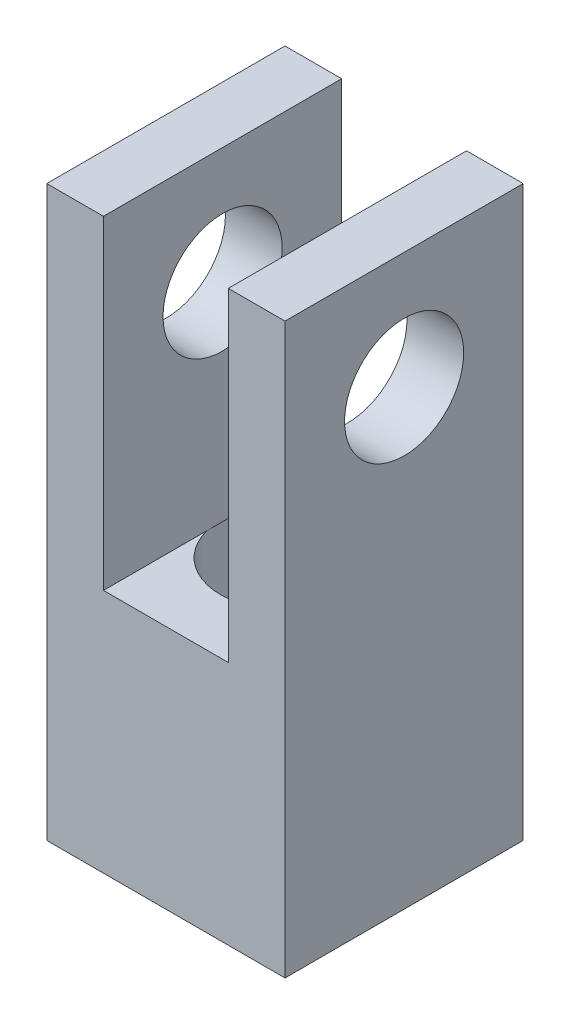
SolidWorks part; units mm, degrees
ref_plane "Front Plane" through (0, 0, 0) normal (0, 0, 1) x (1, 0, 0)
ref_plane "Top Plane" through (0, 0, 0) normal (0, 1, 0) x (1, 0, 0)
ref_plane "Right Plane" through (0, 0, 0) normal (1, 0, 0) x (0, 0, -1)
sketch "Sketch1" plane through (0, 0, 0) normal (0, 1, 0) x (1, 0, 0)
  line L1 (-6.35, -6.35) -> (6.35, -6.35)
  line L2 (-6.35, -6.35) -> (-6.35, 6.35)
  line L3 (-6.35, 6.35) -> (6.35, 6.35)
  line L4 (6.35, -6.35) -> (6.35, 6.35)
  line L5 (-6.35, -6.35) -> (6.35, 6.35) construction
  line L6 (-6.35, 6.35) -> (6.35, -6.35) construction
  point P0 (0, 0)
  dimension "D1" = 12.7
  dimension "D2" = 12.7
extrude "Boss-Extrude1" add sketch "Sketch1" along normal blind 30.3276
sketch "Sketch2" plane through (0, 30.3276, 0) normal (0, 1, 0) x (1, 0, 0)
  line L0 (6.35, 6.35) -> (-6.35, 6.35) construction
  line L1 (-3.3274, -6.35) -> (3.3274, -6.35)
  line L2 (-3.3274, -6.35) -> (-3.3274, 6.35)
  line L3 (-3.3274, 6.35) -> (3.3274, 6.35)
  line L4 (3.3274, -6.35) -> (3.3274, 6.35)
  line L5 (-3.3274, -6.35) -> (3.3274, 6.35) construction
  line L6 (-3.3274, 6.35) -> (3.3274, -6.35) construction
  point P0 (0, 0)
  dimension "D1" = 6.6548
extrude "Cut-Extrude1" cut sketch "Sketch2" against normal blind 17.272
sketch "Sketch3" plane through (6.35, 0, 0) normal (1, 0, 0) x (0, 0, -1)
  line L0 (0, 30.3276) -> (0, 0) construction
  line L1 (-6.35, 30.3276) -> (6.35, 30.3276) construction
  circle A0 centre (0, 24.1046) radius 3.175
  dimension "D1" = 6.35
  dimension "D2" = 6.223
extrude "Cut-Extrude2" cut sketch "Sketch3" against normal through all
sketch "Sketch4" plane through (0, 0, 0) normal (0, -1, 0) x (1, 0, 0)
  circle A0 centre (0, 0) radius 3.429
  dimension "D1" = 6.858
extrude "Cut-Extrude3" cut sketch "Sketch4" against normal up to surface (13.0556 mm away) up to face at (0, 13.0556, 0)
